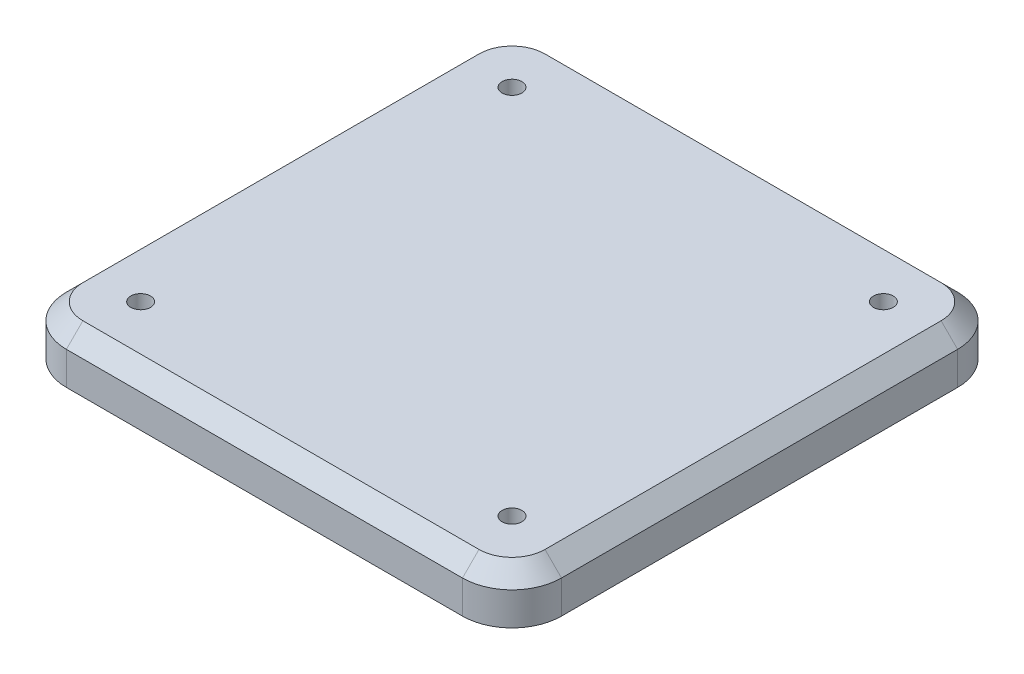
SolidWorks part; units mm, degrees
ref_plane "前基準面" through (0, 0, 0) normal (0, 0, 1) x (1, 0, 0)
ref_plane "上基準面" through (0, 0, 0) normal (0, 1, 0) x (1, 0, 0)
ref_plane "右基準面" through (0, 0, 0) normal (1, 0, 0) x (0, 0, -1)
ref_plane "平面1"
sketch "草圖1" plane through (0, 0, 0) normal (0, 1, 0) x (-1, 0, 0)
  line L0 (0, 0) -> (-300, 0)
  line L1 (-300, 0) -> (-300, -300)
  line L2 (-300, -300) -> (0, -300)
  line L3 (0, -300) -> (0, 0)
  dimension "D1" = 300
  dimension "D2" = 300
extrude "擠出1" add sketch "草圖1" along normal blind 30
fillet "圓角1" radius 30 4 edges at (300, 15, -300) (0, 15, -300) (0, 15, 0) (300, 15, 0)
chamfer "倒角1" distance 10 distance2 10 8 edges at (291.2132, 30, -8.7868) (150, 30, 0) (8.7868, 30, -8.7868) (0, 30, -150) (8.7868, 30, -291.2132) (150, 30, -300) (291.2132, 30, -291.2132) (300, 30, -150)
hole_wizard "孔2" positions "草圖3" profile "草圖2" legacy
sketch "草圖3" plane through (0, 30, 0) normal (0, 1, 0) x (1, 0, 0)
  point P1 (37.5, 37.5)
sketch "草圖2" plane through (37.5, 30, -37.5) normal (1, 0, 0) x (0, 0, 1)
  line L0 (0, 0) -> (0, 13.6052)
  line L1 (0, 13.6052) -> (6, 10)
  line L2 (6, 10) -> (6, 0)
  line L4 (6, 0) -> (0, 0)
  line L6 (0, 13.6052) -> (-6, 10) construction
  line L7 (0, -4.2442) -> (0, 117.3081) construction
  dimension "直徑" = 12
  dimension "深度" = 10
  dimension "導頭角度" = 118
hole_wizard "孔3" positions "草圖5" profile "草圖4" legacy
sketch "草圖5" plane through (0, 0, 0) normal (0, -1, 0) x (-1, 0, 0)
  point P1 (-25, 25)
sketch "草圖4" plane through (25, 0, -25) normal (1, 0, 0) x (0, 0, -1)
  line L0 (0, 0) -> (0, 13.6052)
  line L1 (0, 13.6052) -> (6, 10)
  line L2 (6, 10) -> (6, 0)
  line L4 (6, 0) -> (0, 0)
  line L6 (0, 13.6052) -> (-6, 10) construction
  line L7 (0, -4.2442) -> (0, 117.3081) construction
  dimension "直徑" = 12
  dimension "深度" = 10
  dimension "導頭角度" = 118
ref_plane "平面2" through (30, 0, -150) normal (0, 0, 1) x (1, 0, 0)
mirror "鏡射1" about plane through (30, 0, -150) normal (0, 0, 1) of "孔3", "孔2"
ref_plane "平面3" through (150, 0, -30) normal (1, 0, 0) x (0, 0, -1)
mirror "鏡射2" about plane through (150, 0, -30) normal (1, 0, 0) of "鏡射1", "孔3", "孔2"
